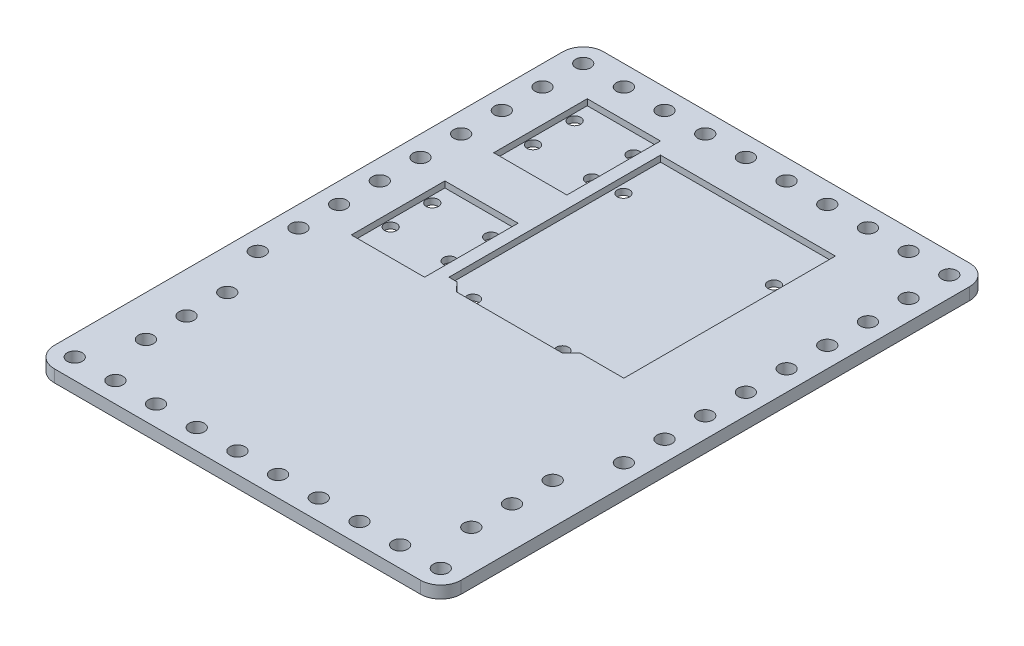
SolidWorks part; units mm, degrees
material "Copper"
ref_plane "Front Plane" through (0, 0, 0) normal (0, 0, 1) x (1, 0, 0)
ref_plane "Top Plane" through (0, 0, 0) normal (0, 1, 0) x (1, 0, 0)
ref_plane "Right Plane" through (0, 0, 0) normal (1, 0, 0) x (0, 0, -1)
sketch "Sketch1" plane through (0, 0, 0) normal (0, 1, 0) x (1, 0, 0)
  line L1 (6.35, 0) -> (120.65, 0)
  line L2 (0, 6.35) -> (0, 165.1)
  line L3 (6.35, 171.45) -> (120.65, 171.45)
  line L4 (127, 6.35) -> (127, 165.1)
  arc A0 (6.35, 0) -> (0, 6.35) centre (6.35, 6.35) cw
  arc A1 (120.65, 0) -> (127, 6.35) centre (120.65, 6.35) ccw
  arc A2 (120.65, 171.45) -> (127, 165.1) centre (120.65, 165.1) cw
  arc A3 (0, 165.1) -> (6.35, 171.45) centre (6.35, 165.1) cw
  point P7 (0, 0)
  point P10 (127, 0)
  point P13 (127, 171.45)
  point P16 (0, 171.45)
  dimension "D3" = 6.35
  dimension "D1" = 127
  dimension "D2" = 171.45
extrude "Plate Extrude" add sketch "Sketch1" along normal blind 3.81
sketch "Sketch2" plane through (0, 3.81, 0) normal (0, 1, 0) x (1, 0, 0)
  line L0 (120.65, 171.45) -> (6.35, 171.45) construction
  line L1 (0, 165.1) -> (0, 6.35) construction
  line L2 (6.35, 0) -> (120.65, 0) construction
  line L3 (63.5, 171.45) -> (63.5, 0) construction
  circle A0 centre (6.35, 165.1) radius 2.3495
  circle A1 centre (19.05, 165.1) radius 2.3495
  circle A2 centre (31.75, 165.1) radius 2.3495
  circle A3 centre (44.45, 165.1) radius 2.3495
  circle A4 centre (57.15, 165.1) radius 2.3495
  circle A5 centre (69.85, 165.1) radius 2.3495
  circle A6 centre (82.55, 165.1) radius 2.3495
  circle A7 centre (95.25, 165.1) radius 2.3495
  circle A8 centre (107.95, 165.1) radius 2.3495
  circle A9 centre (120.65, 165.1) radius 2.3495
  circle A10 centre (6.35, 152.4) radius 2.3495
  circle A11 centre (120.65, 152.4) radius 2.3495
  circle A12 centre (6.35, 139.7) radius 2.3495
  circle A13 centre (120.65, 139.7) radius 2.3495
  circle A14 centre (6.35, 127) radius 2.3495
  circle A15 centre (120.65, 127) radius 2.3495
  circle A16 centre (6.35, 114.3) radius 2.3495
  circle A17 centre (120.65, 114.3) radius 2.3495
  circle A18 centre (6.35, 101.6) radius 2.3495
  circle A19 centre (120.65, 101.6) radius 2.3495
  circle A20 centre (6.35, 88.9) radius 2.3495
  circle A21 centre (120.65, 88.9) radius 2.3495
  circle A22 centre (6.35, 76.2) radius 2.3495
  circle A23 centre (120.65, 76.2) radius 2.3495
  circle A24 centre (6.35, 63.5) radius 2.3495
  circle A25 centre (120.65, 63.5) radius 2.3495
  circle A26 centre (6.35, 6.35) radius 2.3495
  circle A27 centre (19.05, 6.35) radius 2.3495
  circle A28 centre (31.75, 6.35) radius 2.3495
  circle A29 centre (44.45, 6.35) radius 2.3495
  circle A30 centre (57.15, 6.35) radius 2.3495
  circle A31 centre (69.85, 6.35) radius 2.3495
  circle A32 centre (82.55, 6.35) radius 2.3495
  circle A33 centre (95.25, 6.35) radius 2.3495
  circle A34 centre (107.95, 6.35) radius 2.3495
  circle A35 centre (120.65, 6.35) radius 2.3495
  circle A36 centre (12.7, 22.225) radius 2.3495
  circle A37 centre (12.7, 34.925) radius 2.3495
  circle A38 centre (12.7, 47.625) radius 2.3495
  circle A39 centre (114.3, 47.625) radius 2.3495
  circle A40 centre (114.3, 34.925) radius 2.3495
  circle A41 centre (114.3, 22.225) radius 2.3495
  dimension "D1" = 4.699
  dimension "D2" = 6.35
  dimension "D6" = 4.699
  dimension "D7" = 6.35
  dimension "D8" = 6.35
  dimension "D10" = 4.699
  dimension "D11" = 12.7
  dimension "D12" = 22.225
  dimension "D3" = 6.35
  dimension "D4" = 10
  dimension "D5" = 9
  dimension "D9" = 10
  dimension "D13" = 3
extrude "Outer Hole Cut" cut sketch "Sketch2" against normal through all
sketch "Sketch3" plane through (0, 3.81, 0) normal (0, 1, 0) x (1, 0, 0)
  line L0 (81.28, 83.566) -> (84.074, 86.36)
  line L1 (43.18, 152.4) -> (97.79, 152.4)
  line L2 (43.18, 152.4) -> (43.18, 86.36)
  line L3 (43.18, 86.36) -> (97.79, 86.36)
  line L4 (97.79, 152.4) -> (97.79, 86.36)
  line L5 (81.28, 83.566) -> (48.26, 83.566)
  line L6 (48.26, 83.566) -> (45.72, 86.36)
  line L7 (127, 6.35) -> (127, 165.1) construction
  line L8 (120.65, 171.45) -> (6.35, 171.45) construction
  circle A0 centre (78.867, 86.106) radius 1.905
  circle A1 centre (50.927, 86.106) radius 1.905
  circle A2 centre (94.107, 136.906) radius 1.905
  circle A3 centre (45.847, 138.176) radius 1.905
  dimension "D1" = 3.81
  dimension "D9" = 52.07
  dimension "D2" = 54.61
  dimension "D3" = 66.04
  dimension "D4" = 40.894
  dimension "D5" = 38.1
  dimension "D6" = 5.08
  dimension "D7" = 27.94
  dimension "D8" = 7.747
  dimension "D10" = 50.8
  dimension "D11" = 15.24
  dimension "D12" = 5.08
  dimension "D13" = 2.54
  dimension "D14" = 2.794
  dimension "D15" = 2.54
  dimension "D16" = 29.21
  dimension "D17" = 19.05
extrude "Arduino Shape Cut" cut sketch "Sketch3" against normal blind 1.905 contours A1 L3 A0 L4 L1 L2 A3 A2 | A1 L3 L6 L5 L0 A0
sketch "Sketch4" plane through (0, 3.81, 0) normal (0, 1, 0) x (1, 0, 0)
  line L0 (43.18, 152.4) -> (43.18, 86.36) construction
  line L1 (16.51, 127) -> (39.37, 127)
  line L2 (16.51, 127) -> (16.51, 156.21)
  line L3 (16.51, 156.21) -> (39.37, 156.21)
  line L4 (39.37, 127) -> (39.37, 156.21)
  line L5 (43.18, 152.4) -> (97.79, 152.4) construction
  line L6 (16.51, 82.55) -> (39.37, 82.55)
  line L7 (16.51, 82.55) -> (16.51, 111.76)
  line L8 (39.37, 82.55) -> (39.37, 111.76)
  line L9 (16.51, 111.76) -> (39.37, 111.76)
  circle A0 centre (18.6057, 137.1834) radius 1.905
  circle A1 centre (18.6057, 150.1829) radius 1.905
  circle A2 centre (37.005, 150.1829) radius 1.905
  circle A3 centre (37.005, 137.1834) radius 1.905
  circle A4 centre (18.6057, 92.7334) radius 1.905
  circle A5 centre (18.6057, 105.7329) radius 1.905
  circle A6 centre (37.005, 105.7329) radius 1.905
  circle A7 centre (37.005, 92.7334) radius 1.905
  dimension "D1" = 3.81
  dimension "D9" = 18.3993
  dimension "D2" = 22.86
  dimension "D3" = 29.21
  dimension "D4" = 10.1834
  dimension "D5" = 2.365
  dimension "D6" = 3.81
  dimension "D7" = 12.9995
  dimension "D8" = 3.81
  dimension "D10" = 2
extrude "HG7881 Cut" cut sketch "Sketch4" against normal blind 1.905 contours L1 L4 L3 L2 A3 A2 A1 A0 | L9 L7 L6 L8 A7 A6 A5 A4
sketch "Sketch5" plane through (0, 3.81, 0) normal (0, 1, 0) x (1, 0, 0)
  circle A0 centre (94.107, 136.906) radius 1.905 construction
  circle A1 centre (78.867, 86.106) radius 1.905 construction
  circle A2 centre (50.927, 86.106) radius 1.905 construction
  circle A3 centre (45.847, 138.176) radius 1.905 construction
  circle A4 centre (18.6057, 150.1829) radius 1.905 construction
  circle A5 centre (37.005, 150.1829) radius 1.905 construction
  circle A6 centre (37.005, 137.1834) radius 1.905 construction
  circle A7 centre (18.6057, 137.1834) radius 1.905 construction
  circle A8 centre (18.6057, 105.7329) radius 1.905 construction
  circle A9 centre (18.6057, 92.7334) radius 1.905 construction
  circle A10 centre (37.005, 92.7334) radius 1.905 construction
  circle A11 centre (37.005, 105.7329) radius 1.905 construction
  circle A12 centre (94.107, 136.906) radius 1.905
  circle A13 centre (78.867, 86.106) radius 1.905
  circle A14 centre (50.927, 86.106) radius 1.905
  circle A15 centre (45.847, 138.176) radius 1.905
  circle A16 centre (18.6057, 150.1829) radius 1.905
  circle A17 centre (37.005, 150.1829) radius 1.905
  circle A18 centre (37.005, 137.1834) radius 1.905
  circle A19 centre (18.6057, 137.1834) radius 1.905
  circle A20 centre (18.6057, 105.7329) radius 1.905
  circle A21 centre (18.6057, 92.7334) radius 1.905
  circle A22 centre (37.005, 92.7334) radius 1.905
  circle A23 centre (37.005, 105.7329) radius 1.905
extrude "Arduino and HG7881 Hole Cut" cut sketch "Sketch5" against normal through all
